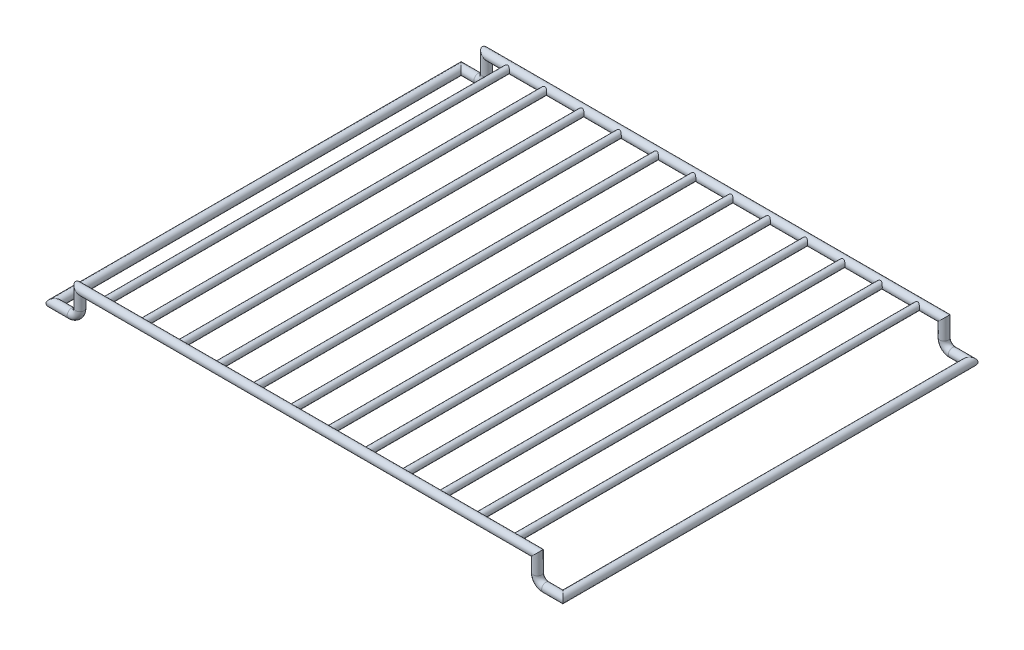
SolidWorks part; units mm, degrees
ref_plane "Front Plane" through (0, 0, 0) normal (0, 0, 1) x (1, 0, 0)
ref_plane "Top Plane" through (0, 0, 0) normal (0, 1, 0) x (1, 0, 0)
ref_plane "Right Plane" through (0, 0, 0) normal (1, 0, 0) x (0, 0, -1)
sketch3d "3DSketch1"
  line L0 (0, 0, 0) -> (135, 0, 0)
  line L1 (135, 0, 0) -> (135, -10, 0)
  line L2 (140, -15, 0) -> (150, -15, 0)
  line L3 (150, -15, 0) -> (150, -15, -240)
  line L4 (150, -15, -240) -> (140, -15, -240)
  line L5 (135, -10, -240) -> (135, 0, -240)
  line L6 (135, 0, -240) -> (0, 0, -240)
  arc A0 (140, -15, -240) -> (135, -10, -240) centre (140, -10, -240) ccw
  arc A1 (135, -10, 0) -> (140, -15, 0) centre (140, -10, 0) ccw
  point P11 (135, -15, -240)
  point P12 (140, -10, -245)
  point P15 (135, -15, 0)
  point P16 (140, -10, 5)
  dimension "D8" = 5
  dimension "D1" = 135
  dimension "D2" = 15
  dimension "D3" = 15
  dimension "D4" = 240
  dimension "D5" = 15
  dimension "D6" = 15
  dimension "D7" = 135
sketch "Sketch1" plane through (0, 0, 0) normal (1, 0, 0) x (0, 0, -1)
  circle A0 centre (0, 0) radius 2.5
  dimension "D1" = 5
sweep "Sweep1" add profiles "Sketch1" path "3DSketch1"
sketch "Sketch2" plane through (0, 0, 0) normal (0, 0, 1) x (1, 0, 0)
  line L0 (0, 2.5) -> (0, -2.5) construction
  circle A0 centre (11, 0) radius 2
  dimension "D2" = 4
  dimension "D1" = 11
extrude "Boss-Extrude1" add sketch "Sketch2" against normal up to surface (237.5 mm away)
pattern_linear "LPattern1" count 6 spacing 22 along (1, 0, 0) of "Boss-Extrude1"
mirror "Mirror1" about plane through (0, 0, -240) normal (-1, 0, 0) of bodies 103
